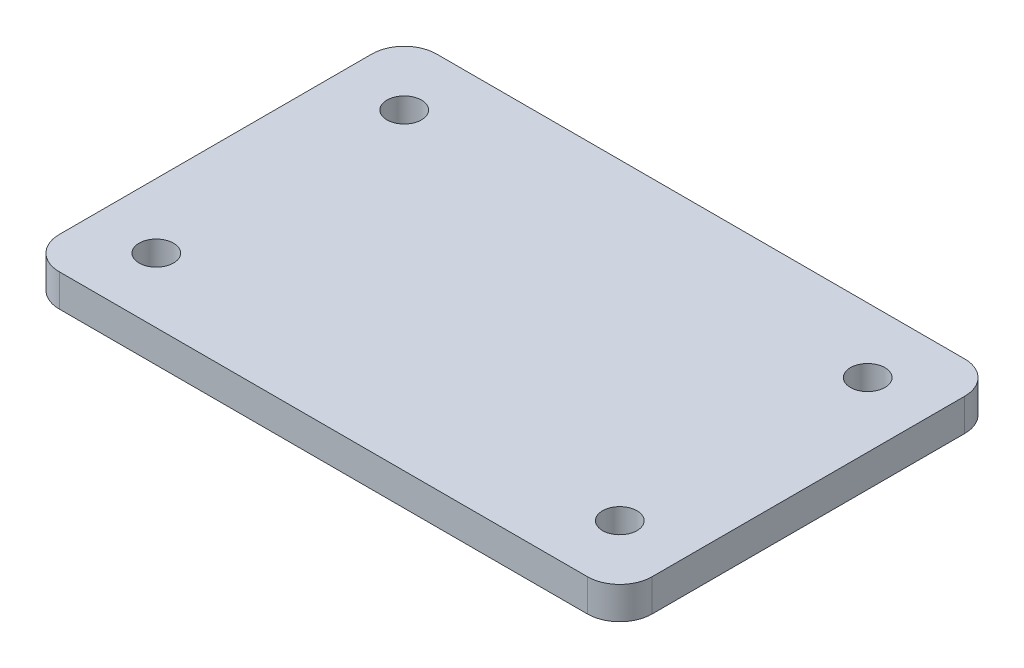
SolidWorks part; units mm, degrees
ref_plane "前视基准面" through (0, 0, 0) normal (0, 0, 1) x (1, 0, 0)
ref_plane "上视基准面" through (0, 0, 0) normal (0, 1, 0) x (1, 0, 0)
ref_plane "右视基准面" through (0, 0, 0) normal (1, 0, 0) x (0, 0, -1)
other "Configuration Table"
sketch "草图1" plane through (0, 0, 0) normal (0, 1, 0) x (1, 0, 0)
  line L1 (0, 0) -> (55, 0)
  line L2 (0, 0) -> (0, 35)
  line L3 (0, 35) -> (55, 35)
  line L4 (55, 0) -> (55, 35)
  dimension "D1" = 55
  dimension "D2" = 35
extrude "凸台-拉伸1" add sketch "草图1" along normal blind 3
sketch "草图2" plane through (0, 3, 0) normal (0, 1, 0) x (1, 0, 0)
  line L0 (49, 29) -> (49, 35) construction
  line L1 (6, 29) -> (49, 29) construction
  line L2 (6, 29) -> (6, 6) construction
  line L3 (6, 6) -> (49, 6) construction
  line L4 (49, 29) -> (49, 6) construction
  line L5 (55, 35) -> (0, 35) construction
  line L6 (49, 6) -> (49, 0) construction
  line L7 (0, 0) -> (55, 0) construction
  line L8 (49, 6) -> (55, 6) construction
  line L9 (55, 0) -> (55, 35) construction
  line L10 (6, 6) -> (0, 6) construction
  line L11 (0, 35) -> (0, 0) construction
  circle A0 centre (6, 29) radius 1.6
  circle A1 centre (49, 29) radius 1.6
  circle A2 centre (49, 6) radius 1.6
  circle A3 centre (6, 6) radius 1.6
  dimension "D1" = 3.2
  dimension "D2" = 3.2
  dimension "D3" = 3.2
  dimension "D4" = 3.2
  dimension "D5" = 23
  dimension "D6" = 43
  dimension "D7" = 180
extrude "切除-拉伸1" cut sketch "草图2" against normal blind 3
fillet "圆角1" radius 3 4 edges at (55, 1.5, -35) (0, 1.5, -35) (0, 1.5, 0) (55, 1.5, 0)
